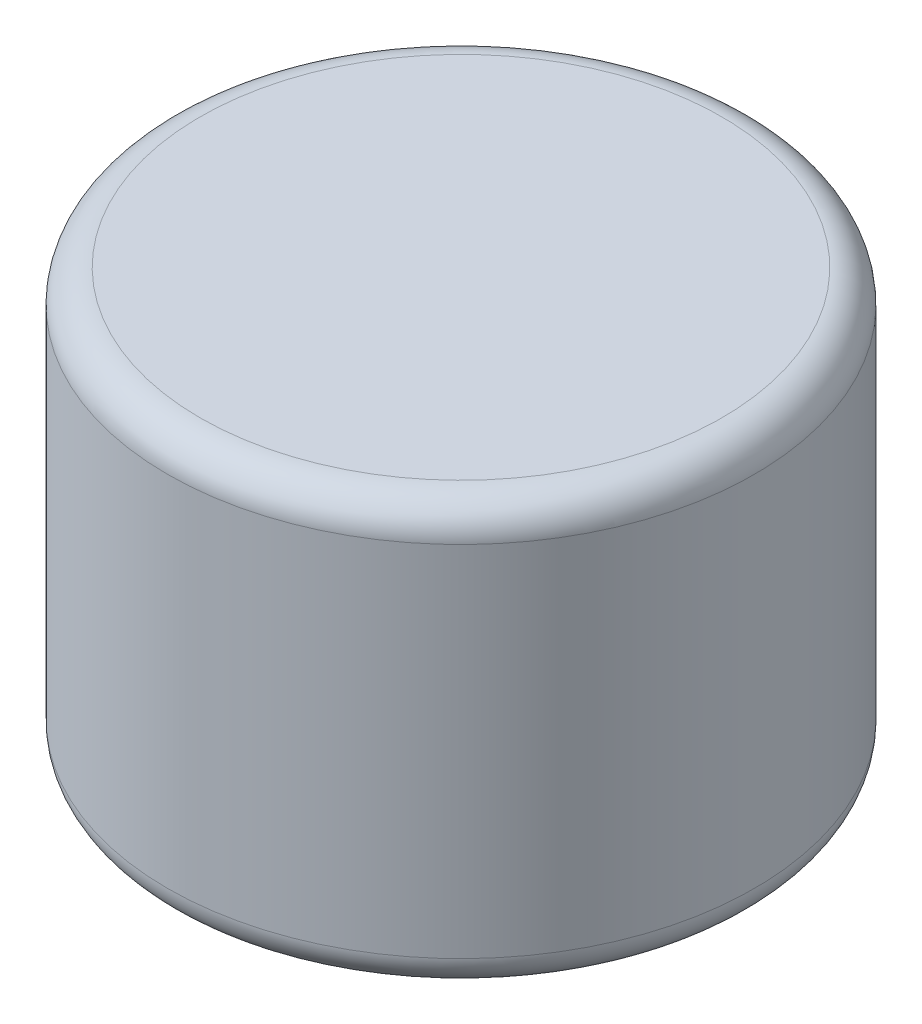
SolidWorks part; units mm, degrees
ref_plane "Front Plane" through (0, 0, 0) normal (0, 0, 1) x (1, 0, 0)
ref_plane "Top Plane" through (0, 0, 0) normal (0, 1, 0) x (1, 0, 0)
ref_plane "Right Plane" through (0, 0, 0) normal (1, 0, 0) x (0, 0, -1)
sketch "Sketch1" plane through (0, 0, 0) normal (0, 1, 0) x (1, 0, 0)
  line L0 (-3.0237, 0.4) -> (3.0237, 0.4)
  line L1 (3.0237, -0.4) -> (-3.0237, -0.4)
  circle A0 centre (0, 0) radius 3.05
  circle A1 centre (0, 0) radius 3.5
  dimension "D1" = 6.1
  dimension "D2" = 7
  dimension "D3" = 0.4
extrude "Boss-Extrude1" add sketch "Sketch1" along normal blind 7
sketch "Sketch2" plane through (0, 7, 0) normal (0, 1, 0) x (1, 0, 0)
  circle A0 centre (0, 0) radius 9
  dimension "D1" = 18
extrude "Boss-Extrude2" add sketch "Sketch2" along normal blind 4
sketch "Sketch3" plane through (0, 7, 0) normal (0, -1, 0) x (1, 0, 0)
  circle A0 centre (0, 0) radius 7
  circle M3 centre (0, 0) radius 9
  dimension "D1" = 14
extrude "Boss-Extrude3" add sketch "Sketch3" along normal blind 9 contours A0 M3
fillet "Fillet1" radius 1 4 edges at (0, -2, -9) (0, 11, 9) (0, 7, 3.5) (0, 7, -7)
chamfer "Chamfer1" [suppressed] distance 1
